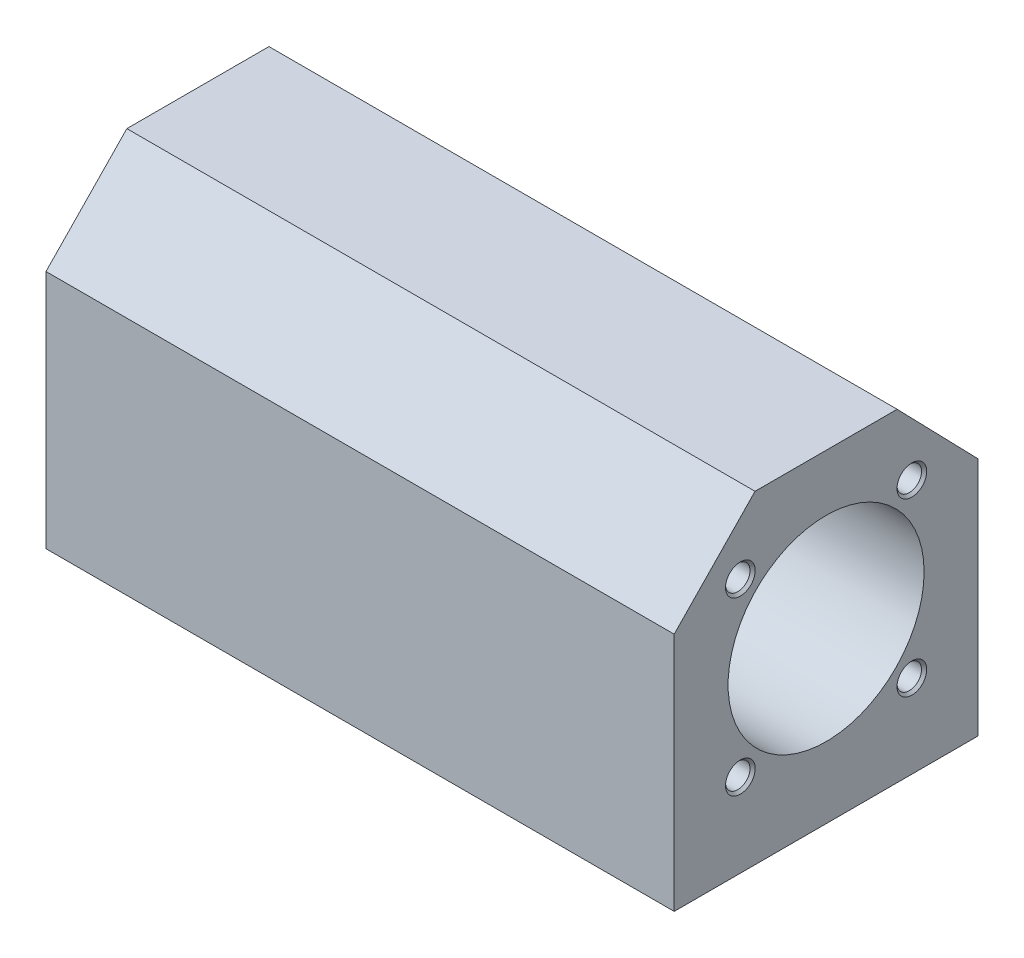
SolidWorks part; units mm, degrees
ref_plane "Plano frontal" through (0, 0, 0) normal (0, 0, 1) x (1, 0, 0)
ref_plane "Plano superior" through (0, 0, 0) normal (0, 1, 0) x (1, 0, 0)
ref_plane "Plano direito" through (0, 0, 0) normal (1, 0, 0) x (0, 0, -1)
sketch "Esboço1" plane through (0, 0, 0) normal (1, 0, 0) x (0, 0, -1)
  line L0 (0, 49) -> (16.5, 66)
  line L1 (0, 0) -> (62, 0)
  line L2 (0, 0) -> (0, 49)
  line L4 (62, 0) -> (62, 49)
  line L5 (16.5, 66) -> (45.5, 66)
  line L6 (45.5, 66) -> (62, 49)
  line L7 (31, 0) -> (31, 66) construction
  point P5 (31, 66)
  point P10 (45.5, 66)
  point P11 (62, 53.4663)
  dimension "D1" = 66
  dimension "D2" = 49
  dimension "D3" = 62
  dimension "D4" = 29
extrude "Ressalto-extrusão1" add sketch "Esboço1" against normal blind 128.2
hole_wizard "Furo roscado de M61" positions "Esboço2" profile "Esboço3" tap size "M6" standard "ISO"
sketch "Esboço2" plane through (0, 0, 0) normal (1, 0, 0) x (0, 0, -1)
  line L0 (0, 0) -> (62, 0) construction
  line L1 (45.5, 66) -> (16.5, 66) construction
  point P0 (13.5, 52)
  point P2 (48.5, 52)
  point P4 (48.5, 17)
  point P6 (13.5, 17)
  point P14 (31, 66)
  dimension "D1" = 35
  dimension "D2" = 35
  dimension "D3" = 17
  dimension "D4" = 17.5
sketch "Esboço3" plane through (0, 52, -13.5) normal (0, 1, 0) x (0, 0, -1)
  line L0 (0, 0) -> (0, 21.9522)
  line L1 (0, 21.9522) -> (2.5, 20.45)
  line L2 (2.5, 20.45) -> (2.5, 0.525)
  line L3 (2.5, 0.525) -> (3.025, 0)
  line L5 (3.025, 0) -> (0, 0)
  line L6 (-2.5, 0.525) -> (-3.025, 0) construction
  line L10 (0, 21.9522) -> (-2.5, 20.45) construction
  line L11 (0, -6.35) -> (0, 107.95) construction
  dimension "Tap Drill Dia." = 5
  dimension "Tap Drill Depth" = 20.45
  dimension "Near C'Sink Dia." = 6.05
  dimension "Near C'Sink Angle" = 90
  dimension "Drill Angle" = 118
sketch "Esboço4" plane through (0, 0, 0) normal (1, 0, 0) x (0, 0, -1)
  circle A0 centre (31, 34.5) radius 12.5
  circle A1 centre (13.5, 52) radius 2.5 construction
  circle A2 centre (48.5, 17) radius 3.025 construction
  dimension "D1" = 25
  dimension "D2" = 17.5
  dimension "D3" = 17.5
extrude "Corte-extrusão1" cut sketch "Esboço4" against normal through all
sketch "Esboço5" plane through (-128.2, 0, 0) normal (-1, 0, 0) x (0, 0, 1)
  circle A0 centre (-31, 34.5) radius 29
  circle A1 centre (-31, 34.5) radius 12.5 construction
  dimension "D1" = 58
extrude "Corte-extrusão2" cut sketch "Esboço5" against normal blind 50
sketch "Esboço6" plane through (0, 0, 0) normal (1, 0, 0) x (0, 0, -1)
  circle A0 centre (31, 34.5) radius 20
  dimension "D1" = 40
extrude "Corte-extrusão3" cut sketch "Esboço6" against normal blind 70
